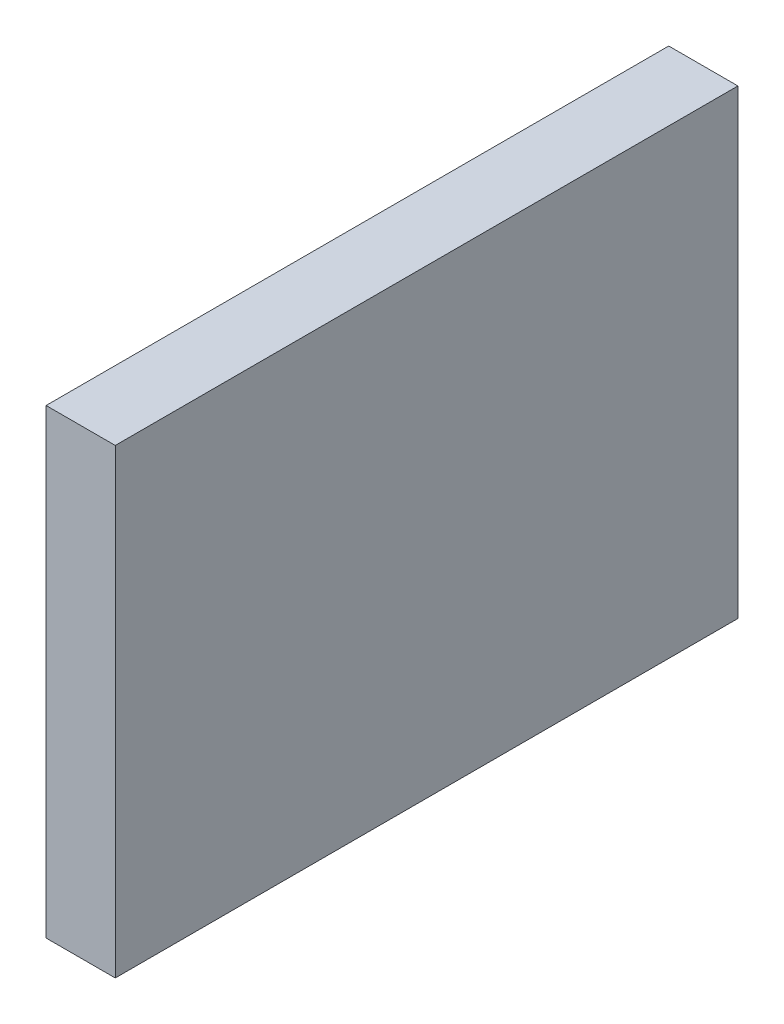
SolidWorks part; units mm, degrees
material "Pine"
ref_plane "Front Plane" through (0, 0, 0) normal (0, 0, 1) x (1, 0, 0)
ref_plane "Top Plane" through (0, 0, 0) normal (0, 1, 0) x (1, 0, 0)
ref_plane "Right Plane" through (0, 0, 0) normal (1, 0, 0) x (0, 0, -1)
sketch "Sketch1" plane through (0, 0, 0) normal (0, 0, 1) x (1, 0, 0)
  line L1 (-10.7051, 15.4676) -> (8.3449, 15.4676)
  line L2 (-10.7051, 15.4676) -> (-10.7051, -111.5324)
  line L3 (-10.7051, -111.5324) -> (8.3449, -111.5324)
  line L4 (8.3449, 15.4676) -> (8.3449, -111.5324)
  dimension "D1" = 19.05
  dimension "D2" = 127
extrude "Boss-Extrude1" add sketch "Sketch1" along normal blind 171.45
